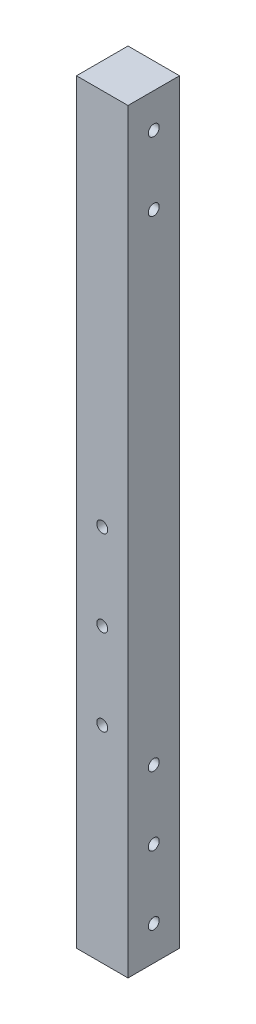
SolidWorks part; units mm, degrees
ref_plane "前视基准面" through (0, 0, 0) normal (0, 0, 1) x (1, 0, 0)
ref_plane "上视基准面" through (0, 0, 0) normal (0, 1, 0) x (1, 0, 0)
ref_plane "右视基准面" through (0, 0, 0) normal (1, 0, 0) x (0, 0, -1)
sketch "草图1" plane through (0, 0, 0) normal (0, 1, 0) x (1, 0, 0)
  line L1 (0, 0) -> (15, 0)
  line L2 (0, 0) -> (0, 15)
  line L3 (0, 15) -> (15, 15)
  line L4 (15, 0) -> (15, 15)
  dimension "D1" = 15
extrude "凸台-拉伸1" add sketch "草图1" along normal blind 220
sketch "草图2" plane through (0, 0, 0) normal (0, 0, 1) x (1, 0, 0)
  line L0 (7.5, -9.7245) -> (7.5, 230.1249) construction
  line L1 (0, 0) -> (15, 0) construction
  circle A0 centre (7.5, 60) radius 1.6
  circle A1 centre (7.5, 85) radius 1.6
  circle A2 centre (7.5, 110) radius 1.6
  dimension "D2" = 25
  dimension "D3" = 25
  dimension "D4" = 60
  dimension "D5" = 3.2
  dimension "D1" = 7.5
extrude "切除-拉伸1" cut sketch "草图2" against normal through all
sketch "草图3" plane through (0, 0, 0) normal (-1, 0, 0) x (0, 0, 1)
  line L0 (0, 220) -> (0, 0) construction
  line L1 (-15, 0) -> (0, 0) construction
  line L2 (-7.5, 242.2996) -> (-7.5, -98.4656) construction
  line L3 (-15, 220) -> (0, 220) construction
  circle A0 centre (-7.5, 50) radius 1.6
  circle A1 centre (-7.5, 10) radius 1.6
  circle A2 centre (-7.5, 30) radius 1.6
  circle A3 centre (-7.5, 210) radius 1.6
  circle A4 centre (-7.5, 190) radius 1.6
  dimension "D1" = 3.2
  dimension "D2" = 7.5
  dimension "D3" = 50
  dimension "D4" = 7.5
  dimension "D5" = 10
  dimension "D6" = 7.5
  dimension "D7" = 20
  dimension "D8" = 10
  dimension "D9" = 20
extrude "切除-拉伸2" cut sketch "草图3" against normal through all both and the other way through all
